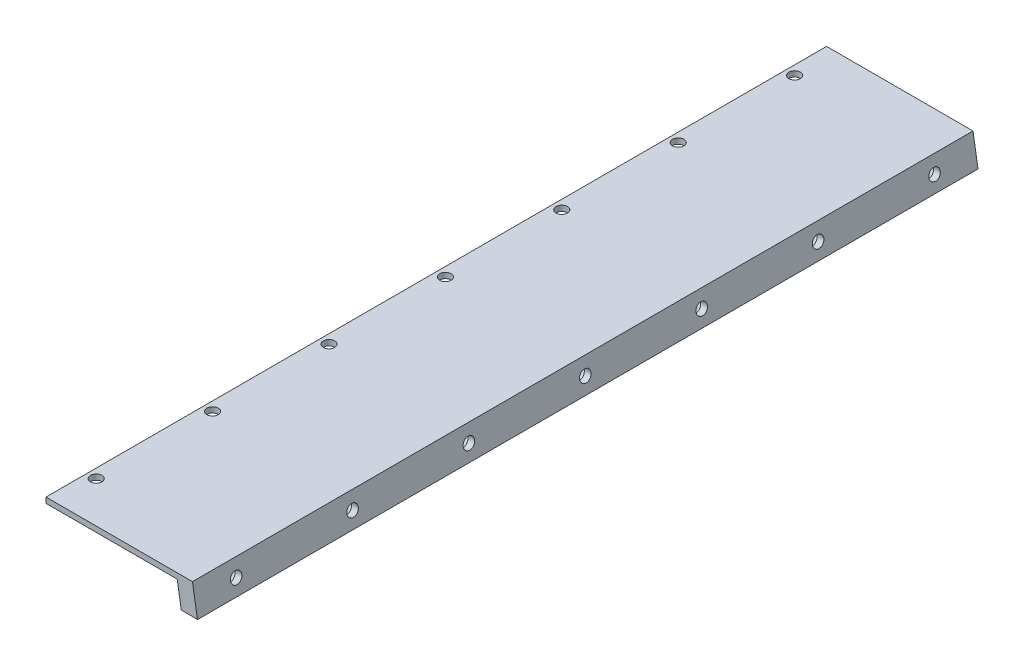
SolidWorks part; units mm, degrees
ref_plane "Front Plane" through (0, 0, 0) normal (0, 0, 1) x (1, 0, 0)
ref_plane "Top Plane" through (0, 0, 0) normal (0, 1, 0) x (1, 0, 0)
ref_plane "Right Plane" through (0, 0, 0) normal (1, 0, 0) x (0, 0, -1)
sketch "Sketch1" plane through (0, 0, 0) normal (0, 0, 1) x (1, 0, 0)
  line L0 (0, 0) -> (32.09, 0)
  line L1 (32.09, 0) -> (33.1785, -6.6617)
  line L2 (0, -1.2) -> (28.7397, -1.2)
  line L3 (28.7397, -1.2) -> (29.6248, -6.617)
  line L4 (0, 0) -> (0, -1.2)
  line L5 (33.1785, -6.6617) -> (29.6248, -6.617)
  dimension "D1" = 1.2
  dimension "D2" = 3.5
  dimension "D3" = 6.75
  dimension "D4" = 80
  dimension "D5" = 99.28
  dimension "D6" = 32.09
extrude "Boss-Extrude1" add sketch "Sketch1" along normal blind 171
sketch "Sketch2" plane through (0, 0, 0) normal (0, 1, 0) x (1, 0, 0)
  line L0 (32.09, 0) -> (0, 0) construction
  line L1 (0, -171) -> (0, 0) construction
  circle A0 centre (2, -9) radius 1.25
  dimension "D1" = 9
  dimension "D2" = 2
  dimension "D3" = 2.5
extrude "Cut-Extrude1" cut sketch "Sketch2" against normal blind 50 contours A0
sketch "Sketch3" plane through (31.2555, 5.1071, 0) normal (0.9869, 0.1613, 0) x (0, 0, -1)
  line L0 (0, -11.9248) -> (0, -5.1748) construction
  line L1 (-171, -11.9248) -> (0, -11.9248) construction
  circle A0 centre (-9, -8.6748) radius 1.25
  dimension "D1" = 9
  dimension "D2" = 2.5
  dimension "D3" = 3.25
extrude "Cut-Extrude2" cut sketch "Sketch3" against normal blind 50 contours A0
sketch "Sketch4" plane through (27.8013, 4.5427, 0) normal (-0.9869, -0.1613, 0) x (0, 0, 1)
  line L1 (7.8164, -6.6248) -> (6.6329, -8.6748)
  line L2 (6.6329, -8.6748) -> (7.8164, -10.7248)
  line L3 (7.8164, -10.7248) -> (10.1836, -10.7248)
  line L4 (10.1836, -10.7248) -> (11.3671, -8.6748)
  line L5 (11.3671, -8.6748) -> (10.1836, -6.6248)
  line L6 (10.1836, -6.6248) -> (7.8164, -6.6248)
  circle A0 centre (9, -8.6748) radius 2.05 construction
  dimension "D1" = 4.1
extrude "Cut-Extrude3" cut sketch "Sketch4" against normal blind 2
pattern_linear "LPattern1" count 7 spacing 25.5 along (0, 0, 1) of "Cut-Extrude1", "Cut-Extrude3", "Cut-Extrude2"
